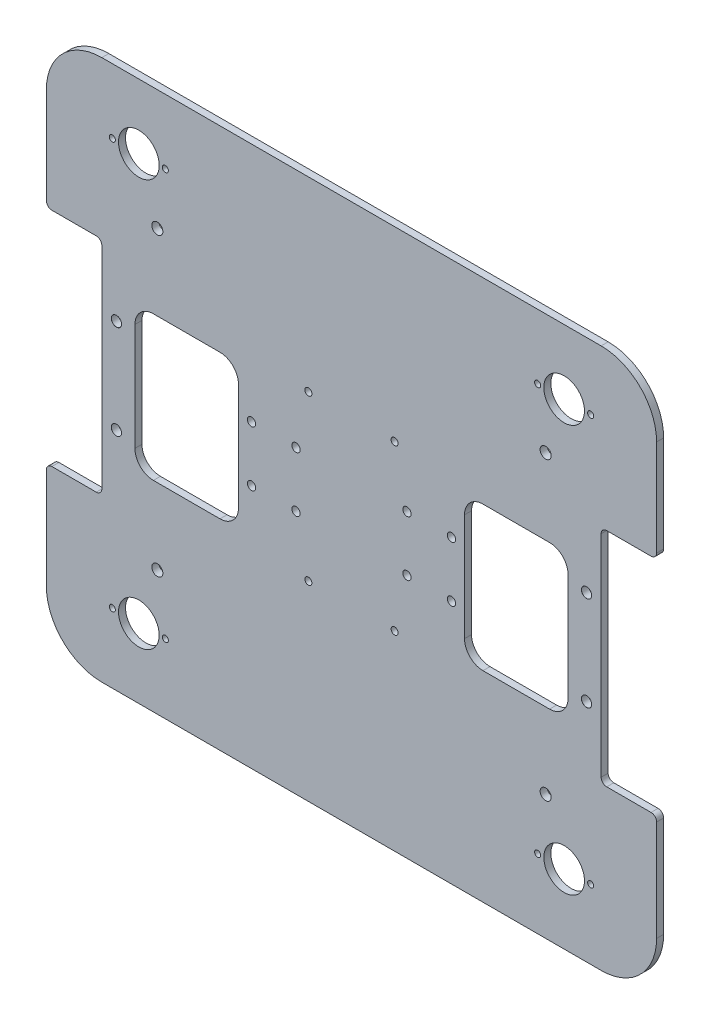
SolidWorks part; units mm, degrees
ref_plane "Front Plane" through (0, 0, 0) normal (0, 0, 1) x (1, 0, 0)
ref_plane "Top Plane" through (0, 0, 0) normal (0, 1, 0) x (1, 0, 0)
ref_plane "Right Plane" through (0, 0, 0) normal (1, 0, 0) x (0, 0, -1)
ref_plane "Plane1" through (0, 150, 0) normal (0, 1, 0) x (1, 0, 0)
ref_plane "Plane2" through (0, -150, 0) normal (0, 1, 0) x (1, 0, 0)
ref_plane "Plane3" through (150, 0, 0) normal (1, 0, 0) x (0, 0, -1)
ref_plane "Plane4" through (-150, 0, 0) normal (1, 0, 0) x (0, 0, -1)
sketch "Sketch2" plane through (0, 0, 0) normal (0, 0, 1) x (1, 0, 0)
  line L0 (0, -10.2) -> (0, 50.0764) construction
  line L1 (-175, 150) -> (175, 150) construction
  line L2 (-175, 150) -> (-175, -150) construction
  line L3 (-175, -150) -> (175, -150) construction
  line L4 (175, 150) -> (175, -150) construction
  line L5 (-175, 150) -> (175, -150) construction
  line L6 (-175, -150) -> (175, 150) construction
  line L7 (165, 115) -> (165, 63)
  line L8 (-135, 145) -> (-71.564, 145)
  line L11 (135, 145) -> (71.564, 145)
  line L12 (-165, 115) -> (-165, 63)
  line L23 (0, 0) -> (25.5983, 0) construction
  line L24 (100.6652, 110) -> (129.3348, 110) construction
  line L25 (-162, -60) -> (-138, -60)
  line L26 (162, 60) -> (138, 60)
  line L28 (162, -60) -> (138, -60)
  line L29 (135, 57) -> (135, -57)
  line L30 (165, 3.917) -> (135, -60) construction
  line L31 (164.3049, -2.436) -> (135, 60) construction
  line L32 (-135, 57) -> (-135, -57)
  line L33 (-162, 60) -> (-138, 60)
  line L35 (165, -63) -> (165, -117.5)
  line L36 (-165, -63) -> (-165, -117.5)
  line L38 (-135, -147.5) -> (135, -147.5)
  line L39 (-71.564, 145) -> (71.564, 145)
  line L42 (-107.12, 38.95) -> (-71.12, 38.95)
  line L43 (-117.12, 28.95) -> (-117.12, -29.05)
  line L44 (-107.12, -39.05) -> (-71.12, -39.05)
  line L45 (-61.12, 28.95) -> (-61.12, -29.05)
  line L46 (-70.12, 35.95) -> (-111.12, 35.95) construction
  line L47 (-111.12, -36.05) -> (-70.12, -36.05) construction
  line L48 (61.12, 28.95) -> (61.12, -29.05)
  line L49 (107.12, -39.05) -> (71.12, -39.05)
  line L50 (117.12, 28.95) -> (117.12, -29.05)
  line L51 (107.12, 38.95) -> (71.12, 38.95)
  circle A0 centre (0, 155.625) radius 55 construction
  circle A1 centre (-129.3348, 110) radius 1.65
  circle A2 centre (-100.6652, 110) radius 1.65
  circle A3 centre (129.3348, 110) radius 1.65
  circle A4 centre (100.6652, 110) radius 1.65
  circle A5 centre (129.3348, -110) radius 1.65
  circle A6 centre (100.6652, -110) radius 1.65
  circle A7 centre (-129.3348, -110) radius 1.65
  circle A8 centre (-100.6652, -110) radius 1.65
  circle A9 centre (115, 110) radius 11
  circle A10 centre (-115, 110) radius 11
  circle A11 centre (115, -110) radius 11
  circle A12 centre (-115, -110) radius 11
  circle A13 centre (-105, 80) radius 3
  circle A14 centre (105, 80) radius 3
  circle A15 centre (105, -80) radius 3
  circle A16 centre (-105, -80) radius 3
  circle A17 centre (127.1213, -25.5) radius 1.65
  circle A18 centre (127.1213, 25.5) radius 1.65
  circle A19 centre (-127.1213, -25.5) radius 1.65
  circle A20 centre (-127.1213, 25.5) radius 1.65
  arc A21 (-165, -117.5) -> (-135, -147.5) centre (-135, -117.5) ccw
  arc A26 (165, -117.5) -> (135, -147.5) centre (135, -117.5) cw
  circle A27 centre (-30, -14.995) radius 2.25
  circle A32 centre (-30, 14.895) radius 2.25
  circle A33 centre (-54.06, 14.895) radius 2.25
  circle A34 centre (-54.06, -14.995) radius 2.25
  circle A35 centre (54.06, -14.995) radius 2.25
  circle A36 centre (30, -14.995) radius 2.25
  circle A37 centre (30, 14.895) radius 2.25
  circle A38 centre (54.06, 14.895) radius 2.25
  arc A39 (165, 115) -> (135, 145) centre (135, 115) ccw
  arc A40 (-165, 115) -> (-135, 145) centre (-135, 115) cw
  arc A41 (-117.12, -29.05) -> (-107.12, -39.05) centre (-107.12, -29.05) ccw
  arc A42 (-71.12, -39.05) -> (-61.12, -29.05) centre (-71.12, -29.05) ccw
  arc A43 (-71.12, 38.95) -> (-61.12, 28.95) centre (-71.12, 28.95) cw
  arc A44 (-107.12, 38.95) -> (-117.12, 28.95) centre (-107.12, 28.95) ccw
  arc A45 (107.12, 38.95) -> (117.12, 28.95) centre (107.12, 28.95) cw
  arc A46 (71.12, 38.95) -> (61.12, 28.95) centre (71.12, 28.95) ccw
  arc A47 (71.12, -39.05) -> (61.12, -29.05) centre (71.12, -29.05) cw
  arc A48 (117.12, -29.05) -> (107.12, -39.05) centre (107.12, -29.05) cw
  arc A49 (162, 60) -> (165, 63) centre (162, 63) ccw
  arc A50 (138, 60) -> (135, 57) centre (138, 57) ccw
  arc A51 (162, -60) -> (165, -63) centre (162, -63) cw
  arc A52 (138, -60) -> (135, -57) centre (138, -57) cw
  arc A53 (-138, -60) -> (-135, -57) centre (-138, -57) ccw
  arc A54 (-162, -60) -> (-165, -63) centre (-162, -63) ccw
  arc A55 (-135, 57) -> (-138, 60) centre (-138, 57) ccw
  arc A56 (-162, 60) -> (-165, 63) centre (-162, 63) cw
  circle A57 centre (-23.313, 44.3256) radius 1.9
  circle A58 centre (23.313, 44.3256) radius 1.9
  circle A59 centre (23.313, -44.3256) radius 1.9
  circle A60 centre (-23.313, -44.3256) radius 1.9
  point P0 (0, 0)
  point P17 (0, -147.5)
  point P25 (0, 94.9228)
  point P59 (163.1615, 0)
  point P82 (-165, -147.5)
  point P103 (165, -147.5)
  point P106 (165, 145)
  point P109 (-165, 145)
  point P134 (165, -60)
  point P140 (-135, -60)
  point P143 (-165, -60)
  point P146 (-135, 60)
  dimension "D3" = 110
  dimension "D7" = 24.06
  dimension "D8" = 3.3
  dimension "D9" = 3.3
  dimension "D10" = 22
  dimension "D11" = 6
  dimension "D12" = 60
  dimension "D13" = 65
  dimension "D16" = 51
  dimension "D17" = 7.8787
  dimension "D18" = 3.3
  dimension "D19" = 3.3
  dimension "D6" = 14.3348
  dimension "D20" = 14.3348
  dimension "D21" = 50
  dimension "D23" = 4.5
  dimension "D24" = 4.5
  dimension "D25" = 4.5
  dimension "D26" = 4.5
  dimension "D27" = 30
  dimension "D29" = 29.89
  dimension "D31" = 30
  dimension "D32" = 3
  dimension "D33" = 3
  dimension "D34" = 10
  dimension "D35" = 14.3348
  dimension "D36" = 22
  dimension "D37" = 3.3
  dimension "D38" = 3.3
  dimension "D39" = 14.3348
  dimension "D40" = 3
  dimension "D41" = 3.8
  dimension "D30" = 14.895
  dimension "D1" = 300
  dimension "D2" = 350
  dimension "D4" = 5
  dimension "D5" = 10
  dimension "D14" = 30
  dimension "D15" = 60
  dimension "D22" = 56
  dimension "D28" = 35
extrude "Boss-Extrude1" add sketch "Sketch2" along normal blind 3.8
hole_wizard "M5 Clearance Hole1" positions "3DSketch1" profile "Sketch3" hole size "M5" standard "ISO" end condition through all
sketch3d "3DSketch1"
  line L0 (-127.1213, 25.5, 3.8) -> (-127.1213, 25.5, 0) construction
  line L1 (-127.1213, -25.5, 3.8) -> (-127.1213, -25.5, 0) construction
  line L2 (127.1213, -25.5, 3.8) -> (127.1213, -25.5, 0) construction
  line L3 (127.1213, 25.5, 3.8) -> (127.1213, 25.5, 0) construction
  point P0 (-127.1213, 25.5, 3.8)
  point P4 (-127.1213, -25.5, 3.8)
  point P8 (127.1213, -25.5, 3.8)
  point P12 (127.1213, 25.5, 3.8)
sketch "Sketch3" plane through (-127.1213, 25.5, 3.8) normal (1, 0, 0) x (0, -1, 0)
  line L0 (0, 0) -> (0, 3.8)
  line L1 (0, 3.8) -> (2.75, 3.8)
  line L2 (2.75, 3.8) -> (2.75, 0.025)
  line L3 (2.75, 0.025) -> (2.775, 0)
  line L5 (2.775, 0) -> (0, 0)
  line L6 (-2.75, 0.025) -> (-2.775, 0) construction
  line L11 (0, -6.35) -> (0, 107.95) construction
  dimension "Thru Hole Dia." = 5.5
  dimension "Thru Hole Depth" = 3.8
  dimension "Near C'Sink Dia." = 5.55
  dimension "Near C'Sink Angle" = 90
sketch "Sketch4" plane through (0, 0, 0) normal (0, 0, -1) x (-1, 0, 0)
  circle A0 centre (-0.0211, 0) radius 13.9877
  point P3 (0, 0)
extrude "Boss-Extrude2" add sketch "Sketch4" along normal blind 0.2
